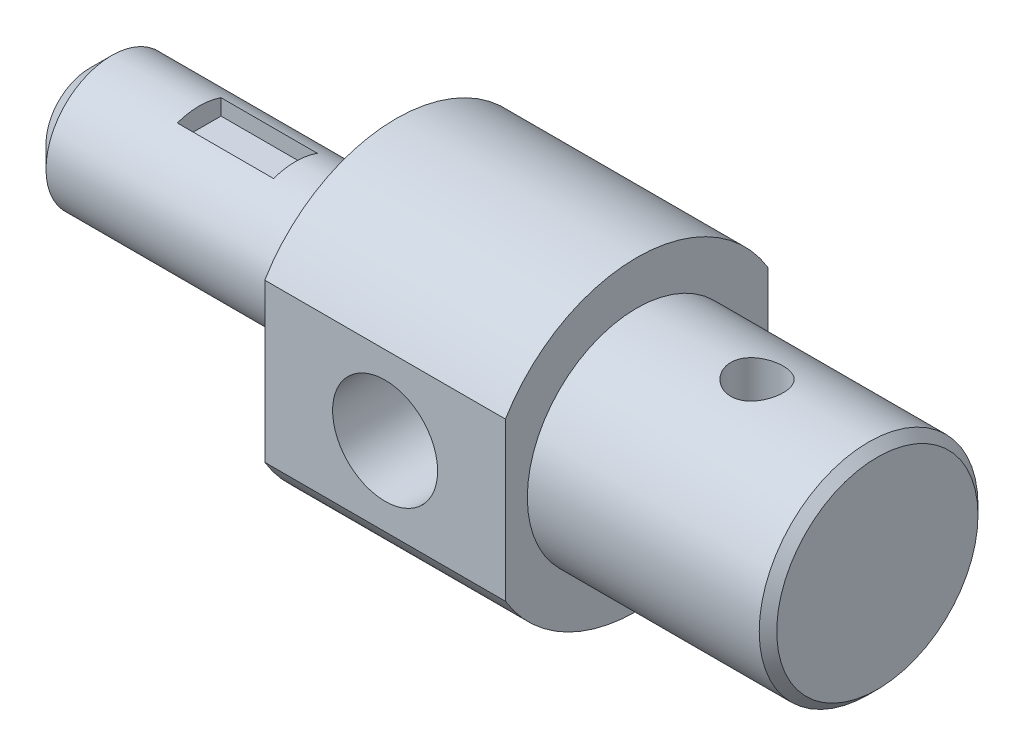
SolidWorks part; units mm, degrees
ref_plane "Спереди" through (0, 0, 0) normal (0, 0, 1) x (1, 0, 0)
ref_plane "Сверху" through (0, 0, 0) normal (0, 1, 0) x (1, 0, 0)
ref_plane "Справа" through (0, 0, 0) normal (1, 0, 0) x (0, 0, -1)
sketch "Эскиз1" plane through (0, 0, 0) normal (0, 0, 1) x (1, 0, 0)
  line L0 (0, 0) -> (-73.2622, 0) construction
  line L1 (0, 0) -> (0, 15)
  line L2 (0, 15) -> (70, 15)
  line L3 (70, 15) -> (70, 35)
  line L4 (70, 35) -> (125, 35)
  line L5 (125, 35) -> (125, 25)
  line L6 (125, 25) -> (180, 25)
  line L7 (180, 25) -> (180, 0)
  line L8 (180, 0) -> (0, 0)
  dimension "D1" = 180
  dimension "D2" = 70
  dimension "D3" = 55
  dimension "D4" = 30
  dimension "D5" = 70
  dimension "D6" = 50
revolve "Повернуть1" add sketch "Эскиз1" angle 360 about L0
sketch "Эскиз2" plane through (125, 0, 0) normal (1, 0, 0) x (0, 0, -1)
  line L0 (-30, 18.0278) -> (-30, -18.0278)
  line L1 (0, 35) -> (0, -35) construction
  circle A0 centre (0, 0) radius 35 construction
  dimension "D1" = 60
extrude "Вырез-Вытянуть1" cut sketch "Эскиз2" against normal through all and the other way through all flip side to cut
mirror "Зеркальное отражение1" about plane through (0, 0, 0) normal (0, 0, 1) of "Вырез-Вытянуть1"
sketch "Эскиз3" plane through (0, 0, 0) normal (0, 0, 1) x (1, 0, 0)
  line L0 (70, 15) -> (0, 15) construction
  line L1 (25, 15) -> (47, 15)
  line L2 (25, 15) -> (25, 10.5)
  line L3 (25, 10.5) -> (47, 10.5)
  line L4 (47, 15) -> (47, 10.5)
  line L5 (0, 15) -> (0, -15) construction
  dimension "D1" = 25
  dimension "D2" = 22
  dimension "D3" = 4.5
extrude "Вырез-Вытянуть2" cut sketch "Эскиз3" against normal mid plane 10
hole_wizard "Диаметр отверстия Ø24.0 (24)1" positions "Эскиз4" profile "Эскиз5" hole size "Ø24.0" standard "ISO" end condition through all
sketch "Эскиз4" plane through (0, 0, 30) normal (0, 0, 1) x (1, 0, 0)
  line L0 (70, 0) -> (125, 0) construction
  line L1 (70, 15) -> (70, -15) construction
  line L2 (125, -25) -> (125, 25) construction
  point P0 (97.5, 0)
  point P11 (0, 0)
  dimension "D1" = 27.5
sketch "Эскиз5" plane through (97.5, 0, 30) normal (1, 0, 0) x (0, -1, 0)
  line L0 (0, 0) -> (0, 60)
  line L1 (0, 60) -> (12, 60)
  line L2 (12, 60) -> (12, 0)
  line L5 (12, 0) -> (0, 0)
  line L11 (0, -6.35) -> (0, 107.95) construction
  dimension "Диаметр сквозного отверстия" = 24
  dimension "Глубина сквозного отверстия" = 60
sketch "Эскиз8" plane through (0, 0, 0) normal (0, 1, 0) x (1, 0, 0)
  line L0 (125, 0) -> (180, 0) construction
  line L1 (125, -25) -> (125, 25) construction
  line L2 (180, -25) -> (180, 25) construction
  circle A0 centre (152.5, 0) radius 6
  point P8 (159.8177, 0)
  point P9 (152.5, 0)
  dimension "D1" = 12
extrude "Вырез-Вытянуть3" cut sketch "Эскиз8" against normal through all both and the other way through all
chamfer "Фаска1" distance 2 angle 45 1 edges at (180, 0, -25)
chamfer "Фаска2" distance 5 angle 45 1 edges at (0, 0, -15)
